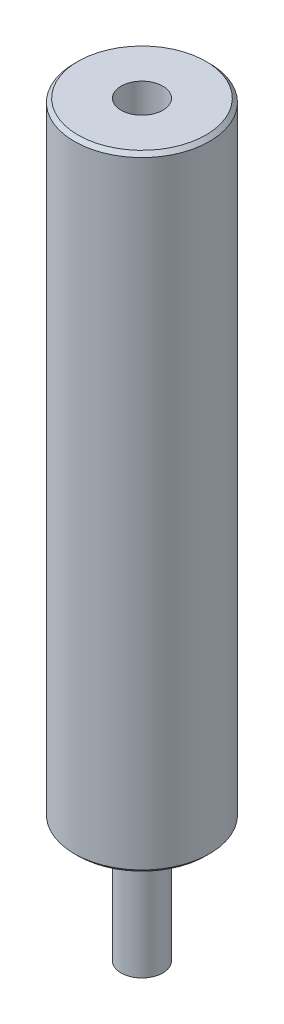
SolidWorks part; units mm, degrees
ref_plane "Plano frontal" through (0, 0, 0) normal (0, 0, 1) x (1, 0, 0)
ref_plane "Plano superior" through (0, 0, 0) normal (0, 1, 0) x (1, 0, 0)
ref_plane "Plano direito" through (0, 0, 0) normal (1, 0, 0) x (0, 0, -1)
ref_plane "Plano1" through (0, 0, 0) normal (0, 0, -1) x (-1, 0, 0)
sketch "Esboço1" plane through (0, 0, 0) normal (0, 0, -1) x (-1, 0, 0)
  line L0 (-1.7, 0) -> (0, 0)
  line L1 (0, 0) -> (0, 50.8)
  line L2 (0, 50.8) -> (-1.7, 50.8)
  line L3 (-1.7, 50.8) -> (-1.7, 60.8)
  line L4 (-1.7, 60.8) -> (-5.2, 60.8)
  line L5 (-5.2, 60.8) -> (-5.5, 60.5)
  line L6 (-5.5, 60.5) -> (-5.5, 10.3)
  line L7 (-5.5, 10.3) -> (-5.2, 10)
  line L8 (-5.2, 10) -> (-2.2, 10)
  line L9 (-1.7, 9.5) -> (-1.7, 0)
  line L10 (0, 0) -> (0, 60.8) construction
  arc A0 (-2.2, 10) -> (-1.7, 9.5) centre (-2.2, 9.5) cw
revolve "Revolução1" add sketch "Esboço1" angle 360 about L10
